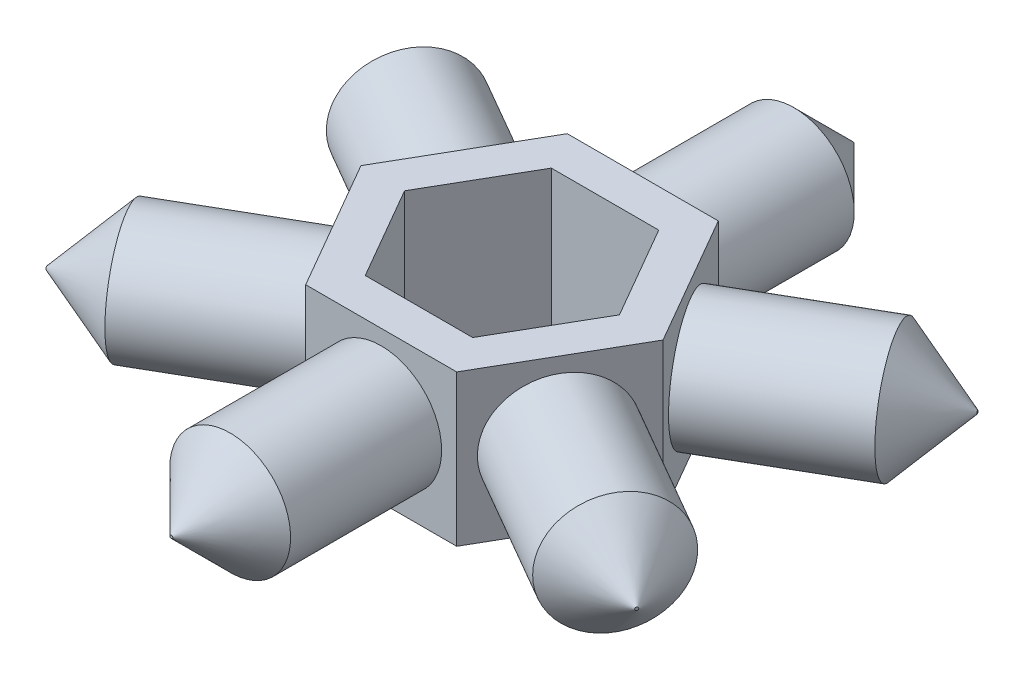
SolidWorks part; units mm, degrees
material "Plain Carbon Steel"
ref_plane "Front Plane" through (0, 0, 0) normal (0, 0, 1) x (1, 0, 0)
ref_plane "Top Plane" through (0, 0, 0) normal (0, 1, 0) x (1, 0, 0)
ref_plane "Right Plane" through (0, 0, 0) normal (1, 0, 0) x (0, 0, -1)
sketch "Sketch1" plane through (0, 0, 0) normal (0, 1, 0) x (1, 0, 0)
  line L0 (-10, 0) -> (0, 0) construction
  line L1 (5, 8.6603) -> (-5, 8.6603)
  line L2 (-5, 8.6603) -> (-10, 0)
  line L3 (-10, 0) -> (-5, -8.6603)
  line L4 (-5, -8.6603) -> (5, -8.6603)
  line L5 (5, -8.6603) -> (10, 0)
  line L6 (10, 0) -> (5, 8.6603)
  line L7 (-7.5, -4.3301) -> (-5.3349, -3.0801) construction
  line L8 (-7.1132, 0) -> (-3.5566, -6.1603)
  line L9 (-3.5566, -6.1603) -> (3.5566, -6.1603)
  line L10 (3.5566, -6.1603) -> (7.1132, 0)
  line L11 (7.1132, 0) -> (3.5566, 6.1603)
  line L12 (3.5566, 6.1603) -> (-3.5566, 6.1603)
  line L13 (-3.5566, 6.1603) -> (-7.1132, 0)
  circle A0 centre (0, 0) radius 8.6603 construction
  circle A1 centre (0, 0) radius 6.1603 construction
  dimension "D1" = 2.5
  dimension "D2" = 10
  dimension "D3" = 12.3205
extrude "Boss-Extrude1" add sketch "Sketch1" along normal mid plane 10
sketch "Sketch2" plane through (0, 0, -8.6603) normal (0, 0, -1) x (-1, 0, 0)
  circle A0 centre (0, 0) radius 4
  dimension "D1" = 8
extrude "Boss-Extrude2" add sketch "Sketch2" along normal blind 10
sketch "Sketch3" plane through (0, 0, 0) normal (1, 0, 0) x (0, 0, -1)
  line L0 (18.6603, 4) -> (22.5603, 0.1)
  line L1 (22.5603, 0.1) -> (22.5603, 0)
  line L2 (22.5603, 0) -> (18.6603, 0)
  line L3 (18.6603, -4) -> (18.6603, 4) construction
  line L4 (18.6603, 0) -> (18.6603, 4)
  line L5 (-981.3397, 0) -> (49018.6603, 0) construction
  point P8 (0, 0)
  point P10 (18.6603, 0)
  point P11 (23.9933, 0)
  dimension "D1" = 0.2
  dimension "D2" = 45
revolve "Revolve1" add sketch "Sketch3" angle 360 about L5
sketch "Sketch6" plane through (7.5, 0, -4.3301) normal (0.866, 0, -0.5) x (-0.5, 0, -0.866)
  circle A0 centre (0, 0) radius 4
  point P3 (0, 0)
  point P4 (0, 0)
  dimension "D1" = 8
extrude "Boss-Extrude3" add sketch "Sketch6" along normal blind 10
sketch "Sketch9" plane through (0, 0, 0) normal (0, 1, 0) x (1, 0, 0)
  line L0 (14.1603, 12.7942) -> (19.4878, 11.3667)
  line L1 (19.4878, 11.3667) -> (19.5378, 11.2801)
  line L2 (19.5378, 11.2801) -> (16.1603, 9.3301)
  line L4 (0, 0) -> (41627.7668, 24033.8024) construction
  line L5 (18.1603, 5.866) -> (14.1603, 12.7942) construction
  line L6 (16.1603, 9.3301) -> (14.1603, 12.7942)
  dimension "D1" = 0.2
  dimension "D2" = 45
revolve "Revolve4" add sketch "Sketch9" angle 360 about L4
sketch "Sketch10" plane through (0, 0, 0) normal (0, 1, 0) x (1, 0, 0)
  line L0 (9.5, -0.866) -> (18.1603, -5.866)
  line L1 (18.1603, -5.866) -> (19.5878, -11.1935)
  line L2 (19.5878, -11.1935) -> (19.5378, -11.2801)
  line L3 (19.5378, -11.2801) -> (7.5, -4.3301)
  line L4 (0, 0) -> (43301.0923, -24999.8973) construction
  line L5 (5, -8.6603) -> (10, 0) construction
  line L6 (9.5, -0.866) -> (7.5, -4.3301)
  dimension "D1" = 8
  dimension "D2" = 0.2
  dimension "D3" = 45
  dimension "D4" = 10
revolve "Revolve5" add sketch "Sketch10" angle 360 about L4
ref_plane "Plane1" through (0, 0, 0) normal (0.866, 0, 0.5) x (0.5, 0, -0.866)
ref_plane "Plane2" through (0, 0, 0) normal (0.866, 0, -0.5) x (-0.5, 0, -0.866)
ref_plane "Plane4" through (0, 0, 0) normal (0, 0, -1) x (-1, 0, 0)
mirror "Mirror1" about plane through (0, 0, 0) normal (0.866, 0, -0.5) of "Revolve4", "Boss-Extrude3"
mirror "Mirror2" about plane through (0, 0, 0) normal (0.866, 0, 0.5) of "Revolve5", "Mirror1"
